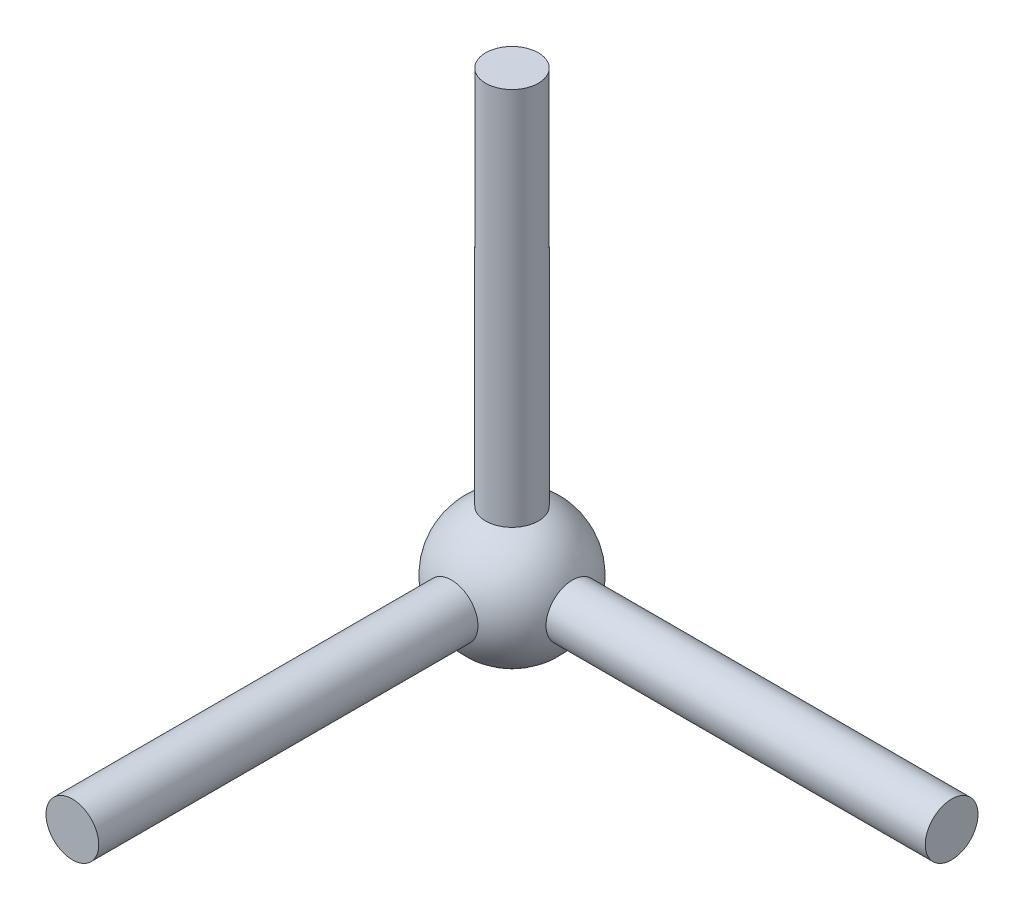
SolidWorks part; units mm, degrees
ref_plane "前视基准面" through (0, 0, 0) normal (0, 0, 1) x (1, 0, 0)
ref_plane "上视基准面" through (0, 0, 0) normal (0, 1, 0) x (1, 0, 0)
ref_plane "右视基准面" through (0, 0, 0) normal (1, 0, 0) x (0, 0, -1)
other "Configuration Table"
sketch "草图4" plane through (0, 0, 0) normal (0, 0, 1) x (1, 0, 0)
  line L0 (0, -7.5) -> (0, 7.5) construction
  line L1 (0, -7.5) -> (0, 7.5)
  arc A0 (0, 7.5) -> (0, -7.5) centre (0, 0) ccw
revolve "旋转10" add sketch "草图4" angle 360 about L0
sketch "草图5" plane through (0, 0, 0) normal (0, 1, 0) x (1, 0, 0)
  circle A0 centre (0, 0) radius 3
extrude "凸台-拉伸1" add sketch "草图5" along normal blind 50
sketch "草图6" plane through (0, 0, 0) normal (0, 0, 1) x (1, 0, 0)
  circle A0 centre (0, 0) radius 3
extrude "凸台-拉伸2" add sketch "草图6" along normal blind 50
sketch "草图7" plane through (0, 0, 0) normal (1, 0, 0) x (0, 0, -1)
  circle A0 centre (0, 0) radius 3
extrude "凸台-拉伸3" add sketch "草图7" along normal blind 50
